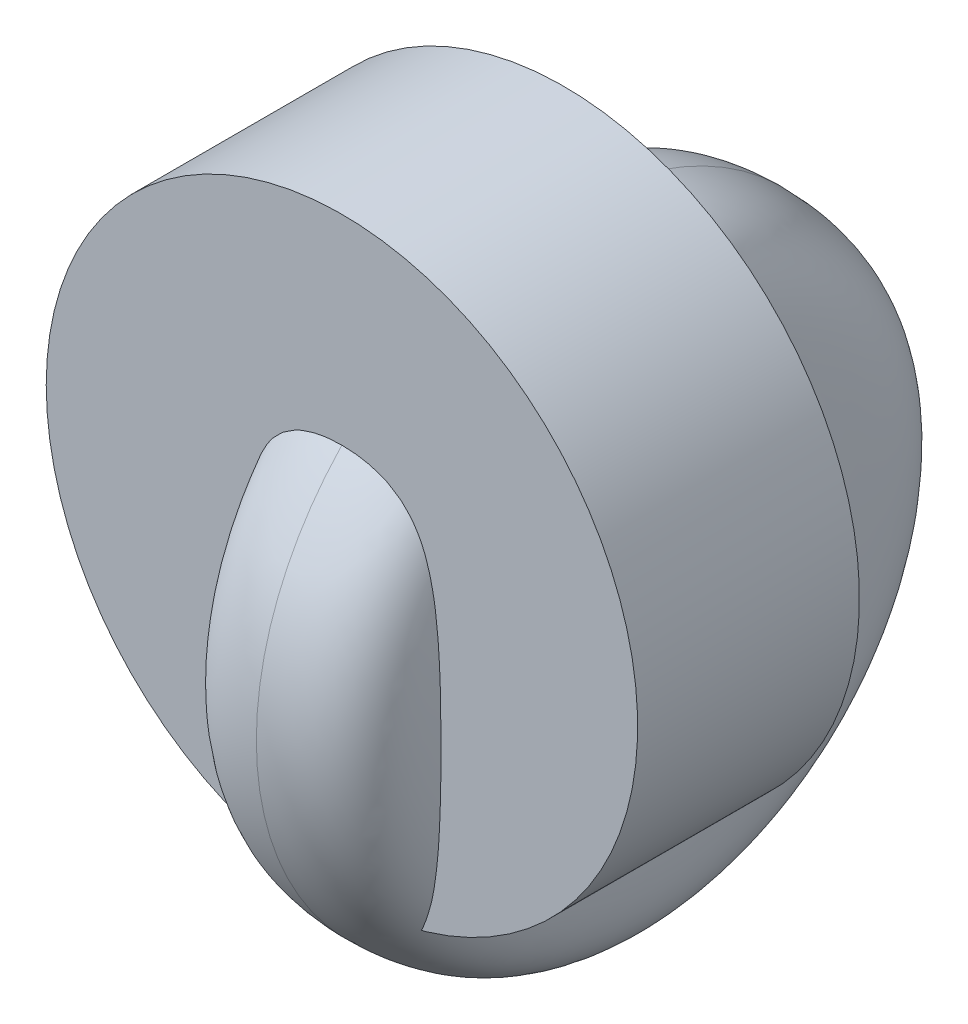
SolidWorks part; units mm, degrees
ref_plane "Front Plane" through (0, 0, 0) normal (0, 0, 1) x (1, 0, 0)
ref_plane "Top Plane" through (0, 0, 0) normal (0, 1, 0) x (1, 0, 0)
ref_plane "Right Plane" through (0, 0, 0) normal (1, 0, 0) x (0, 0, -1)
sketch "Sketch4" plane through (0, 0, 0) normal (0, 0, 1) x (1, 0, 0)
  circle A0 centre (0, 0) radius 101.6
extrude "Boss-Extrude3" add sketch "Sketch4" along normal blind 76.2
sketch "Sketch5" plane through (0, 0, 0) normal (0, 0, -1) x (-1, 0, 0)
  circle A0 centre (0, 0) radius 38.1
extrude "Cut-Extrude2" cut sketch "Sketch5" against normal blind 58.42
sketch "Sketch7" plane through (0, 0, 0) normal (0, 0, 1) x (1, 0, 0)
  line L0 (0, 0) -> (-38.1, 0)
  line L1 (0, 0) -> (38.1, 0)
  line L2 (0, 65.4165) -> (0, 0)
  line L3 (-38.1, 3.7576) -> (38.1, 3.7576)
  line L4 (0, 3.7576) -> (0, 65.4165)
  line L6 (-28.5892, 11.3776) -> (-36.2999, 11.3776)
  line L7 (-36.2999, 11.3776) -> (-28.5892, 11.3776)
  line L8 (28.5892, 11.3776) -> (36.2999, 11.3776)
  line L9 (0, 65.4165) -> (-119.8848, 65.4165)
  line L10 (-119.8848, 65.4165) -> (-119.8848, -145.8106)
  line L11 (-119.8848, -145.8106) -> (169.838, -145.8106)
  line L12 (-119.8848, -40.197) -> (240.0798, -40.197)
  line L13 (-28.5892, 11.3776) -> (28.5892, 11.3776) construction
  line L14 (-22.8744, 16.4576) -> (22.8744, 16.4576)
  line L15 (-22.8744, 16.4576) -> (-22.8744, -11.0834)
  line L16 (-22.8744, -11.0834) -> (24.5499, -11.0834)
  line L17 (24.5499, -11.0834) -> (22.8744, 16.4576)
  line L18 (-22.8744, 16.4576) -> (22.8744, 16.4576)
  spline S0 degree 3 poles (-38.1, 3.7576) (-30.1482, 27.9537) (-44.5712, 64.9241) (0, 65.4165) knots 0 0 0 0 1 1 1 1
  spline S1 degree 3 poles (38.1, 3.7576) (30.1482, 27.9537) (44.5712, 64.9241) (0, 65.4165) knots 0 0 0 0 1 1 1 1
  spline S2 degree 1 poles (28.5892, 11.3776) (0, 57.796) knots 0 0 1 1 construction
  spline S3 degree 1 poles (-28.5892, 11.3776) (0, 57.796) knots 0 0 1 1 construction
  spline S4 degree 3 poles (0, 57.796) (0.5438, 57.7894) (1.6495, 57.763) (3.7135, 57.6627) (6.1214, 57.4506) (8.712, 57.0712) (11.7937, 56.4184) (14.9736, 55.3659) (17.8706, 53.8427) (20.0742, 52.1195) (21.819, 50.1517) (23.2577, 47.8292) (24.8409, 44.1515) (26.2036, 38.4157) (27.0338, 30.1319) (27.4622, 22.5086) (27.9736, 16.2) (28.3542, 12.9736) (28.5892, 11.3776) knots 0.114376 0.114376 0.114376 0.114376 0.128203 0.14203 0.169684 0.197338 0.224992 0.2803 0.335608 0.390916 0.446224 0.501532 0.55684 0.667456 0.778072 0.888688 0.943996 0.999304 0.999304 0.999304 0.999304
  spline S5 degree 3 poles (-28.5892, 11.3776) (-28.3542, 12.9736) (-27.9736, 16.2) (-27.4622, 22.5086) (-27.0338, 30.1319) (-26.2036, 38.4157) (-24.8409, 44.1515) (-23.2577, 47.8292) (-21.819, 50.1517) (-20.0742, 52.1195) (-17.8706, 53.8427) (-14.9736, 55.3659) (-11.7937, 56.4184) (-8.712, 57.0712) (-6.1214, 57.4506) (-3.7135, 57.6627) (-1.6495, 57.763) (-0.5438, 57.7894) (0, 57.796) knots 0.114376 0.114376 0.114376 0.114376 0.169684 0.224992 0.335608 0.446224 0.55684 0.612148 0.667456 0.722764 0.778072 0.83338 0.888688 0.916342 0.943996 0.97165 0.985477 0.999304 0.999304 0.999304 0.999304
  spline S6 degree 1 poles (-22.8744, 16.4576) (0, 52.7156) knots 0 0 1 1 construction
  spline S7 degree 1 poles (22.8744, 16.4576) (0, 52.7156) knots 0 0 1 1 construction
  spline S8 degree 3 poles (0, 52.7156) (-0.4668, 52.7095) (-1.4173, 52.6867) (-3.1807, 52.604) (-5.2235, 52.4337) (-7.3924, 52.1371) (-9.9297, 51.6398) (-12.4575, 50.8701) (-14.6078, 49.8446) (-16.111, 48.7971) (-17.2447, 47.6874) (-18.22, 46.3627) (-19.421, 44.0936) (-20.7047, 40.0445) (-21.5099, 34.4786) (-21.9449, 29.3808) (-22.2181, 25.2899) (-22.4499, 21.6943) (-22.672, 18.7334) (-22.8034, 17.2123) (-22.8744, 16.4576) knots 0.178399 0.178399 0.178399 0.178399 0.191217 0.204035 0.229671 0.255307 0.280943 0.332215 0.383487 0.434759 0.486031 0.537303 0.588575 0.691119 0.793663 0.844935 0.896207 0.947479 0.973115 0.998751 0.998751 0.998751 0.998751
  spline S9 degree 3 poles (22.8744, 16.4576) (22.8034, 17.2123) (22.672, 18.7334) (22.4499, 21.6943) (22.2181, 25.2899) (21.9449, 29.3808) (21.5099, 34.4786) (20.7047, 40.0445) (19.421, 44.0936) (18.22, 46.3627) (17.2447, 47.6874) (16.111, 48.7971) (14.6078, 49.8446) (12.4575, 50.8701) (9.9297, 51.6398) (7.3924, 52.1371) (5.2235, 52.4337) (3.1807, 52.604) (1.4173, 52.6867) (0.4668, 52.7095) (0, 52.7156) knots 0.178399 0.178399 0.178399 0.178399 0.204035 0.229671 0.280943 0.332215 0.383487 0.486031 0.588575 0.639847 0.691119 0.742391 0.793663 0.844935 0.896207 0.921843 0.947479 0.973115 0.985933 0.998751 0.998751 0.998751 0.998751
  dimension "D1" = 38.1
  dimension "D2" = 38.1
  dimension "D4" = 12.7
  dimension "D3" = 7.62
revolve "Revolve1" add sketch "Sketch7" angle 360 about L12
ref_plane "Plane1" through (0, 66.04, 0) normal (0, 1, 0) x (1, 0, 0)
sketch "Sketch13" plane through (0, 66.04, 0) normal (0, 1, 0) x (1, 0, 0)
  line L0 (0, 111.9876) -> (0, -110.4322)
ref_plane "Plane2" through (36.83, 0, 0) normal (1, 0, 0) x (0, 0, -1)
sketch "Sketch14" plane through (36.83, 0, 0) normal (1, 0, 0) x (0, 0, -1)
  line L0 (0, -40.197) -> (-164.5739, -40.197)
  line L1 (0, 65.4165) -> (0, -145.8106) construction
  circle A0 centre (0, -40.197) radius 56.3823
sketch "Sketch23" plane through (36.83, 0, 0) normal (1, 0, 0) x (0, 0, -1)
  circle A0 centre (0, -40.197) radius 51.5746
  circle A1 centre (0, -40.197) radius 41.91
extrude "Boss-Extrude4" add sketch "Sketch23" against normal blind 76.2
sketch "Sketch24" plane through (36.83, 0, 0) normal (1, 0, 0) x (0, 0, -1)
  circle A0 centre (0, -40.197) radius 20.701
  circle A1 centre (0, -40.197) radius 41.91 construction
  circle A2 centre (0, -40.197) radius 41.91
  dimension "D1" = 41.402
extrude "Boss-Extrude5" add sketch "Sketch24" against normal blind 76.2 contours A2 | A0
sketch "Sketch25" plane through (0, 0, 58.42) normal (0, 0, -1) x (-1, 0, 0)
  circle A0 centre (0, 0) radius 20.701
  dimension "D1" = 41.402
extrude "Cut-Extrude8" cut sketch "Sketch25" against normal blind 76.2
